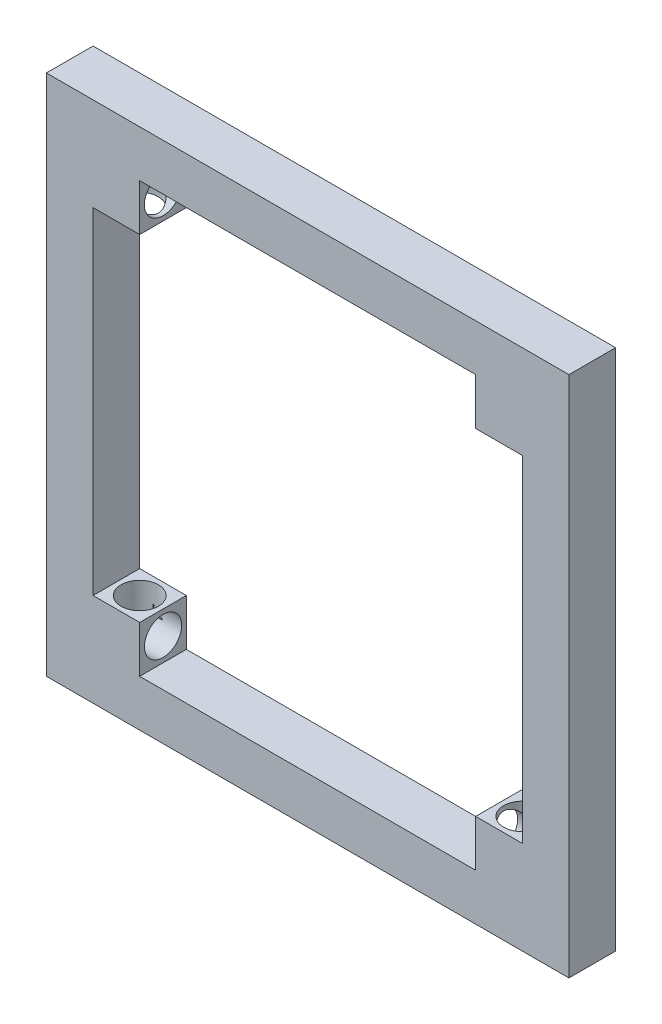
SolidWorks part; units mm, degrees
ref_plane "Alzado" through (0, 0, 0) normal (0, 0, 1) x (1, 0, 0)
ref_plane "Planta" through (0, 0, 0) normal (0, 1, 0) x (1, 0, 0)
ref_plane "Vista lateral" through (0, 0, 0) normal (1, 0, 0) x (0, 0, -1)
sketch "Croquis1" plane through (0, 0, 0) normal (0, 0, 1) x (1, 0, 0)
  line L0 (102, 56) -> (10, 56) construction
  line L1 (0, 0) -> (112, 0)
  line L2 (0, 0) -> (0, 112)
  line L3 (0, 112) -> (112, 112)
  line L4 (112, 0) -> (112, 112)
  line L5 (20, 10) -> (92, 10)
  line L6 (10, 20) -> (10, 92)
  line L7 (20, 102) -> (92, 102)
  line L8 (102, 20) -> (102, 92)
  line L11 (10, 92) -> (20, 92)
  line L12 (20, 102) -> (20, 92)
  line L15 (102, 92) -> (92, 92)
  line L16 (92, 102) -> (92, 92)
  line L17 (102, 20) -> (92, 20)
  line L18 (92, 10) -> (92, 20)
  line L21 (10, 20) -> (20, 20)
  line L22 (20, 10) -> (20, 20)
  dimension "D1" = 10
  dimension "D2" = 10
  dimension "D3" = 10
  dimension "D4" = 10
  dimension "D5" = 72
  dimension "D6" = 10
  dimension "D7" = 72
extrude "Saliente-Extruir1" add sketch "Croquis1" along normal blind 10
sketch "Croquis2" plane through (0, 92, 0) normal (0, -1, 0) x (1, 0, 0)
  line L0 (102, 0) -> (92, 0) construction
  line L1 (92, 10) -> (92, 0) construction
  circle A0 centre (97, 5) radius 4
  point P2 (97, 4.9907)
  point P5 (97, 0)
  point P8 (92, 5)
  dimension "D1" = 8
extrude "Cortar-Extruir1" cut sketch "Croquis2" against normal blind 6
sketch "Croquis3" plane through (92, 0, 0) normal (-1, 0, 0) x (0, 0, 1)
  line L0 (10, 92) -> (10, 102) construction
  line L1 (10, 92) -> (0, 92) construction
  circle A0 centre (5, 97) radius 4
  point P2 (0, 0)
  point P5 (10, 97)
  point P8 (5, 92)
  dimension "D1" = 8
extrude "Cortar-Extruir2" cut sketch "Croquis3" against normal blind 6
ref_plane "Plano1" through (56, 0, 0) normal (-1, 0, 0) x (0, 0, 1)
ref_plane "Plano2" through (0, 56, 0) normal (0, 1, 0) x (1, 0, 0)
mirror "Simetría1" about plane through (56, 0, 0) normal (-1, 0, 0) of "Cortar-Extruir2", "Cortar-Extruir1"
mirror "Simetría2" about plane through (0, 56, 0) normal (0, 1, 0) of "Simetría1", "Cortar-Extruir1", "Cortar-Extruir2"
